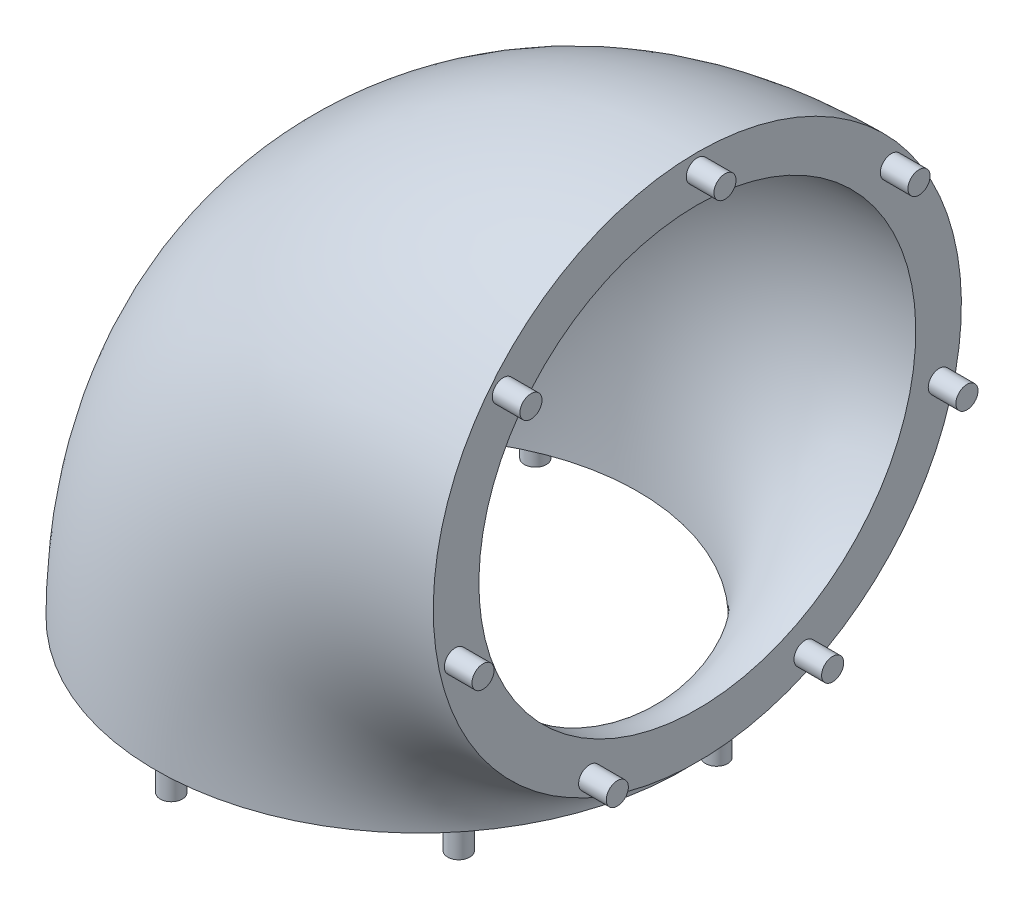
SolidWorks part; units mm, degrees
ref_plane "Alzado" through (0, 0, 0) normal (0, 0, 1) x (1, 0, 0)
ref_plane "Planta" through (0, 0, 0) normal (0, 1, 0) x (1, 0, 0)
ref_plane "Vista lateral" through (0, 0, 0) normal (1, 0, 0) x (0, 0, -1)
sketch "Croquis3" plane through (0, 0, 0) normal (0, 0, 1) x (1, 0, 0)
  line L0 (0, 79) -> (0, 0)
  line L1 (100.5, 179.5) -> (179.5, 179.5)
  arc A0 (0, 79) -> (100.5, 179.5) centre (100.5, 79) cw
  dimension "D1" = 100.5
  dimension "D2" = 79
  dimension "D3" = 79
sketch "Croquis4" plane through (0, 0, 0) normal (0, 1, 0) x (1, 0, 0)
  circle A0 centre (0, 0) radius 95.5
  circle A1 centre (0, 0) radius 79
  dimension "D1" = 191
  dimension "D2" = 158
sweep "Barrer5" add profiles "Croquis4" path "Croquis3"
sketch "Croquis6" plane through (0, 0, 0) normal (0, -1, 0) x (1, 0, 0)
  circle A0 centre (0, 0) radius 79
  circle A1 centre (0, 0) radius 85
  dimension "D1" = 158
  dimension "D2" = 170
extrude "Cortar-Extruir1" cut sketch "Croquis6" against normal blind 79
sketch "Croquis7" plane through (179.5, 0, 0) normal (1, 0, 0) x (0, 0, -1)
  circle A0 centre (0, 179.5) radius 79
  circle A1 centre (0, 179.5) radius 85
  dimension "D1" = 158
  dimension "D2" = 170
extrude "Cortar-Extruir2" cut sketch "Croquis7" against normal blind 79
sketch "Croquis8" plane through (0, 79, 0) normal (0, -1, 0) x (1, 0, 0)
  circle A0 centre (0, 0) radius 95.5
extrude "Cortar-Extruir3" cut sketch "Croquis8" along normal blind 79
sketch "Croquis10" plane through (0, 79, 0) normal (0, -1, 0) x (1, 0, 0)
  line L0 (0, 84) -> (0, 95.5) construction
  circle A0 centre (0, 0) radius 84 construction
  circle A1 centre (0, 0) radius 95.5 construction
  circle A2 centre (0, 0) radius 79 construction
  circle A3 centre (0, 0) radius 89.75 construction
  circle A4 centre (0, 89.75) radius 4
  circle A5 centre (70.1694, 55.9582) radius 4
  circle A6 centre (87.4998, -19.9713) radius 4
  circle A7 centre (38.9411, -80.862) radius 4
  circle A8 centre (-38.9411, -80.862) radius 4
  circle A9 centre (-87.4998, -19.9713) radius 4
  circle A10 centre (-70.1694, 55.9582) radius 4
  point P9 (0, 89.75)
  point P27 (0, 0)
  dimension "D1" = 168
  dimension "D2" = 191
  dimension "D3" = 8
  dimension "D4" = 7
extrude "Saliente-Extruir3" add sketch "Croquis10" along normal blind 10
sketch "Croquis11" plane through (100.5, 0, 0) normal (1, 0, 0) x (0, 0, -1)
  circle A0 centre (0, 179.5) radius 95.5
  circle A1 centre (0, 179.5) radius 79 construction
  dimension "D1" = 191
extrude "Cortar-Extruir4" cut sketch "Croquis11" along normal through all
sketch "Croquis12" plane through (100.5, 0, 0) normal (1, 0, 0) x (0, 0, -1)
  line L0 (0, 275) -> (0, 263.5) construction
  circle A0 centre (0, 179.5) radius 84 construction
  circle A1 centre (0, 179.5) radius 95.5 construction
  circle A2 centre (0, 179.5) radius 89.75 construction
  circle A3 centre (0, 179.5) radius 79 construction
  circle A4 centre (0, 269.25) radius 4
  circle A5 centre (70.1694, 235.4582) radius 4
  circle A6 centre (87.4998, 159.5287) radius 4
  circle A7 centre (38.9411, 98.638) radius 4
  circle A8 centre (-38.9411, 98.638) radius 4
  circle A9 centre (-87.4998, 159.5287) radius 4
  circle A10 centre (-70.1694, 235.4582) radius 4
  point P9 (0, 269.25)
  point P26 (0, 179.5)
  dimension "D1" = 8
  dimension "D2" = 168
  dimension "D3" = 191
  dimension "D4" = 7
extrude "Saliente-Extruir4" add sketch "Croquis12" along normal blind 10
